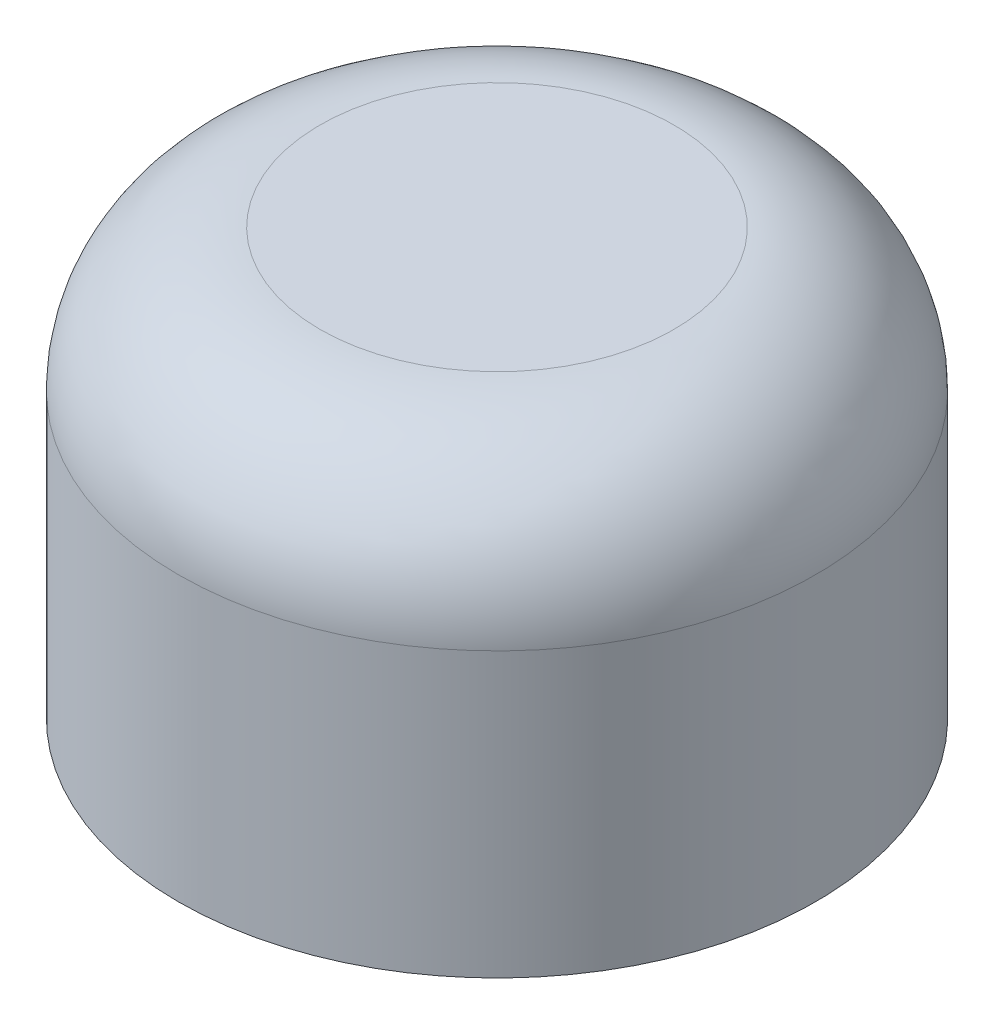
SolidWorks part; units mm, degrees
ref_plane "前视基准面" through (0, 0, 0) normal (0, 0, 1) x (1, 0, 0)
ref_plane "上视基准面" through (0, 0, 0) normal (0, 1, 0) x (1, 0, 0)
ref_plane "右视基准面" through (0, 0, 0) normal (1, 0, 0) x (0, 0, -1)
sketch "草图1" plane through (0, 0, 0) normal (0, 1, 0) x (1, 0, 0)
  circle A0 centre (0, 0) radius 11.25
  dimension "D1" = 22.5
extrude "凸台-拉伸1" add sketch "草图1" along normal blind 15
fillet "圆角1" radius 5 1 edges at (0, 15, 11.25)
sketch "草图2" plane through (0, 0, 0) normal (0, -1, 0) x (1, 0, 0)
  line L1 (-3.65, -3.65) -> (3.65, -3.65)
  line L2 (-3.65, -3.65) -> (-3.65, 3.65)
  line L3 (-3.65, 3.65) -> (3.65, 3.65)
  line L4 (3.65, -3.65) -> (3.65, 3.65)
  line L5 (-3.65, -3.65) -> (3.65, 3.65) construction
  line L6 (-3.65, 3.65) -> (3.65, -3.65) construction
  point P0 (0, 0)
  dimension "D1" = 7.3
  dimension "D2" = 7.3
extrude "切除-拉伸1" cut sketch "草图2" against normal blind 8
